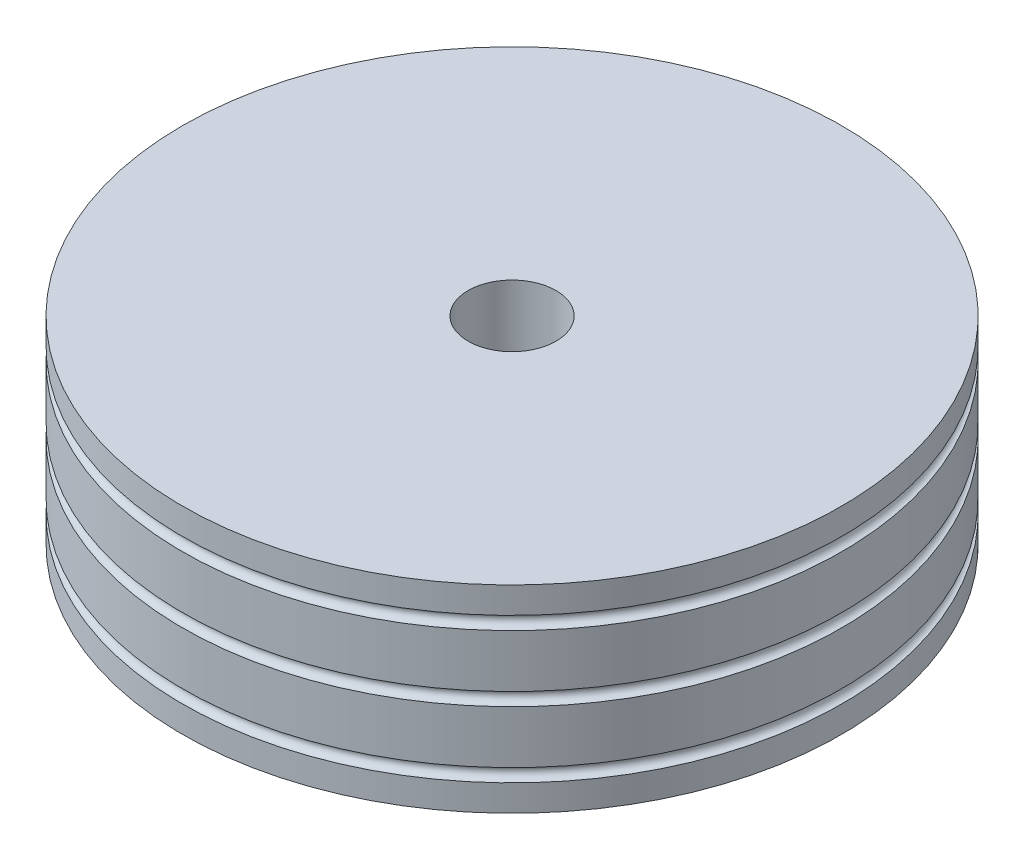
SolidWorks part; units mm, degrees
ref_plane "Front Plane" through (0, 0, 0) normal (0, 0, 1) x (1, 0, 0)
ref_plane "Top Plane" through (0, 0, 0) normal (0, 1, 0) x (1, 0, 0)
ref_plane "Right Plane" through (0, 0, 0) normal (1, 0, 0) x (0, 0, -1)
sketch "Sketch1" plane through (0, 0, 0) normal (0, 0, 1) x (1, 0, 0)
  line L0 (0, 4.5) -> (0, -4.5)
  line L1 (0, 4.5) -> (15, 4.5)
  line L2 (15, 4.5) -> (15, 3.3)
  line L3 (15, -4.5) -> (0, -4.5)
  line L4 (15, 2.7) -> (15, 0.3)
  line L5 (15, -0.3) -> (15, -2.7)
  line L6 (15, -3.3) -> (15, -4.5)
  arc A1 (15, 3.3) -> (15, 2.7) centre (15, 3) ccw
  arc A2 (15, -2.7) -> (15, -3.3) centre (15, -3) ccw
  arc A3 (15, 0.3) -> (15, -0.3) centre (15, 0) ccw
  point P4 (0, 0)
  dimension "D3" = 4.5
  dimension "D1" = 0.3
  dimension "D2" = 3
revolve "Revolve2" add sketch "Sketch1" angle 360 about L0
sketch "Sketch2" plane through (0, 4.5, 0) normal (0, 1, 0) x (1, 0, 0)
  circle A0 centre (0, 0) radius 2
  circle A1 centre (0, 0) radius 15 construction
  dimension "D1" = 4
extrude "Cut-Extrude1" cut sketch "Sketch2" against normal blind 6
sketch "Sketch9" plane through (0, -4.5, 0) normal (0, -1, 0) x (1, 0, 0)
  circle A0 centre (0, 0) radius 3
  circle A1 centre (0, 0) radius 15 construction
  dimension "D1" = 6
extrude "Cut-Extrude2" cut sketch "Sketch9" against normal blind 3
